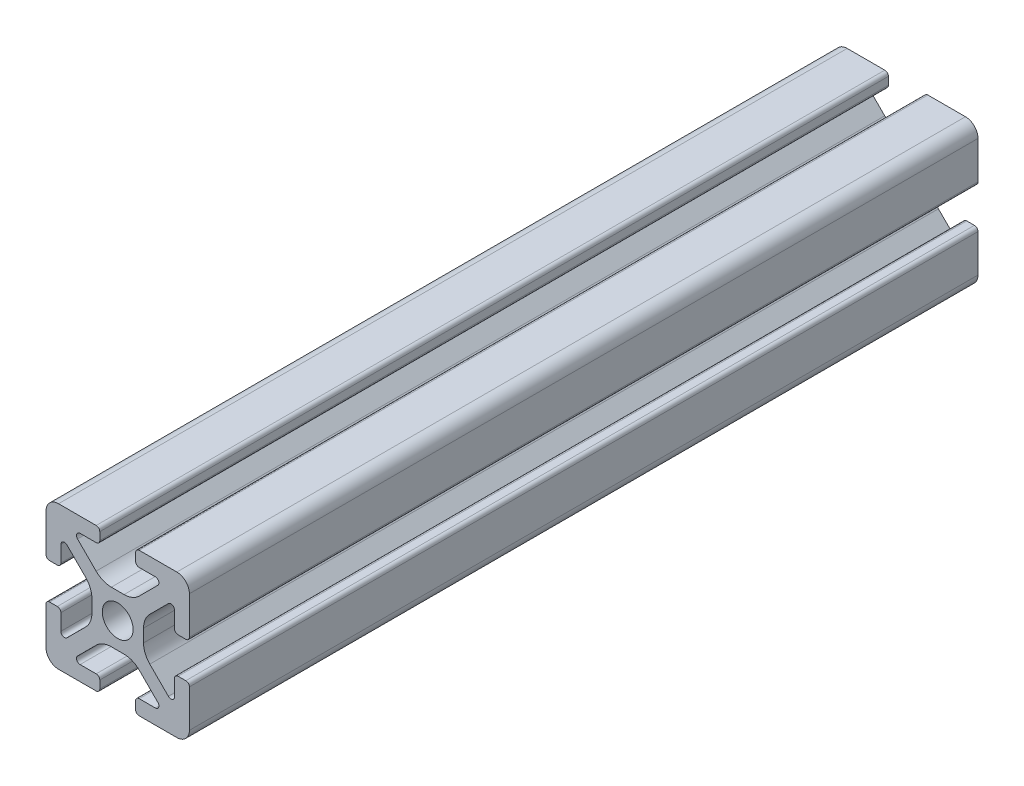
SolidWorks part; units mm, degrees
ref_plane "Front Plane" through (0, 0, 0) normal (0, 0, 1) x (1, 0, 0)
ref_plane "Top Plane" through (0, 0, 0) normal (0, 1, 0) x (1, 0, 0)
ref_plane "Right Plane" through (0, 0, 0) normal (1, 0, 0) x (0, 0, -1)
sketch "Sketch2" plane through (0, 0, 0) normal (0, 0, 1) x (1, 0, 0)
  line L0 (0, 10) -> (0, -10) construction
  line L1 (-10, 0) -> (10, 0) construction
  line L2 (2.5, -10) -> (10, -10)
  line L3 (10, -10) -> (10, -2.5)
  line L4 (2.5, -10) -> (2.5, -7.9246)
  line L5 (2.5, -7.9246) -> (6.4571, -7.9246)
  line L6 (6.4571, -7.9246) -> (2.1325, -3.6)
  line L7 (0, 0) -> (10, -10) construction
  line L8 (10, -2.5) -> (7.9246, -2.5)
  line L9 (7.9246, -2.5) -> (7.9246, -6.4571)
  line L10 (7.9246, -6.4571) -> (3.6, -2.1325)
  line L11 (5.7623, -4.2948) -> (4.2948, -5.7623) construction
  circle A0 centre (0, 0) radius 2.15
  arc A1 (5.25, -7.9246) -> (5.6036, -7.0711) centre (5.25, -7.4246) ccw construction
  point P8 (0, -3.6)
  point P16 (5.0286, -5.0286)
  dimension "Center Hole Diameter" = 4.3
  dimension "D3" = 0.5
  dimension "Rail Height" = 20
  dimension "Rail Width" = 20
  dimension "T-Slot Width" = 5
  dimension "Slot Depth" = 6.4
  dimension "Slot Inner Width" = 11.5
sketch "Sketch3" plane through (0, 0, 0) normal (1, 0, 0) x (0, 0, -1)
  line L0 (-457.2, -10) -> (457.2, -10) construction
  line L1 (-431.8, 0) -> (431.8, 0) construction
  line L2 (0, 10) -> (0, -10) construction
  line L3 (0, 10) -> (0, -10) construction
  point P6 (-431.8, 0)
  point P8 (431.8, 0)
  dimension "Length" = 914.4
  dimension "D1" = 25.4
sketch "Sketch4" plane through (0, 0, 0) normal (0, 0, 1) x (1, 0, 0)
  line L0 (3, -10) -> (8.25, -10)
  line L1 (2.5, -10) -> (10, -10) construction
  line L2 (2.5, -10) -> (2.5, -7.9246) construction
  line L3 (2.5, -7.9246) -> (6.4571, -7.9246) construction
  line L4 (2.5, -8.4246) -> (2.5, -9.5)
  line L5 (3, -7.9246) -> (5.25, -7.9246)
  line L6 (0, -3.6) -> (0.8898, -3.6)
  line L7 (6.4571, -7.9246) -> (2.1325, -3.6) construction
  line L8 (3.0112, -4.4787) -> (5.6036, -7.0711)
  line L9 (10, -10) -> (10, -2.5) construction
  line L10 (7.9246, -6.4571) -> (3.6, -2.1325) construction
  line L11 (7.9246, -2.5) -> (7.9246, -6.4571) construction
  line L12 (7.9246, -5.25) -> (7.9246, -3)
  line L13 (10, -2.5) -> (7.9246, -2.5) construction
  line L14 (8.4246, -2.5) -> (9.5, -2.5)
  line L15 (10, -3) -> (10, -8.25)
  line L16 (7.0711, -5.6036) -> (4.4787, -3.0112)
  line L17 (3.6, 0) -> (3.6, -0.8898)
  line L18 (-10, 0) -> (10, 0) construction
  line L19 (0, -3.6) -> (0, -2.15)
  line L20 (0, 10) -> (0, -10) construction
  line L21 (3.6, 0) -> (2.15, 0)
  arc A0 (2.5, -9.5) -> (3, -10) centre (3, -9.5) ccw
  arc A1 (5.25, -7.9246) -> (5.6036, -7.0711) centre (5.25, -7.4246) ccw construction
  arc A2 (2.5, -8.4246) -> (3, -7.9246) centre (3, -8.4246) cw
  arc A3 (5.25, -7.9246) -> (5.6036, -7.0711) centre (5.25, -7.4246) ccw
  arc A4 (0.8898, -3.6) -> (3.0112, -4.4787) centre (0.8898, -6.6) cw
  arc A5 (8.25, -10) -> (10, -8.25) centre (8.25, -8.25) ccw
  arc A6 (7.0711, -5.6036) -> (7.9246, -5.25) centre (7.4246, -5.25) ccw
  arc A7 (7.9246, -3) -> (8.4246, -2.5) centre (8.4246, -3) cw
  arc A8 (9.5, -2.5) -> (10, -3) centre (9.5, -3) cw
  arc A9 (4.4787, -3.0112) -> (3.6, -0.8898) centre (6.6, -0.8898) cw
  circle A10 centre (0, 0) radius 2.15 construction
  arc A11 (0, -2.15) -> (2.15, 0) centre (0, 0) ccw
  dimension "D1" = 1.75
  dimension "D2" = 3
extrude "Boss-Extrude1" add sketch "Sketch4" along normal mid plane 110
mirror "Mirror1" about plane through (0, 0, 0) normal (1, 0, 0) of bodies 134
mirror "Mirror2" about plane through (0, 0, 0) normal (0, 1, 0) of bodies 135
equation "\"D3@Sketch2\"=\"T-Slot Width@Sketch2\"*0.1"
equation "\"D1@Sketch4\"=\"D3@Sketch2\"*3.5"
equation "\"D2@Sketch4\"=\"D3@Sketch2\"*6"
equation "\"D1@Boss-Extrude1\"=\"Length@Sketch3\""
